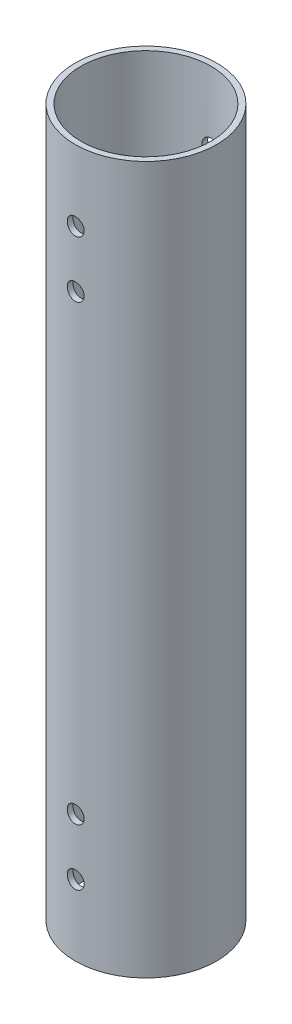
SolidWorks part; units mm, degrees
material "Thornel Mat VMA"
ref_plane "前视基准面" through (0, 0, 0) normal (0, 0, 1) x (1, 0, 0)
ref_plane "上视基准面" through (0, 0, 0) normal (0, 1, 0) x (1, 0, 0)
ref_plane "右视基准面" through (0, 0, 0) normal (1, 0, 0) x (0, 0, -1)
other "Configuration Table"
sketch "草图1" plane through (0, 0, 0) normal (0, 1, 0) x (1, 0, 0)
  circle A0 centre (0, 0) radius 25
  circle A1 centre (0, 0) radius 23
  dimension "D1" = 50
  dimension "D2" = 46
extrude "凸台-拉伸1" add sketch "草图1" along normal blind 250
sketch "草图2" plane through (0, 0, 0) normal (0, 0, 1) x (1, 0, 0)
  line L0 (-1005.3322, 125) -> (48994.6678, 125) construction
  line L1 (-25, 250) -> (-25, 0) construction
  line L2 (25, 0) -> (-25, 0) construction
  line L3 (25, 0) -> (25, 70) construction
  line L4 (25, 70) -> (-25, 70) construction
  line L5 (-25, 0) -> (-25, 70) construction
  line L6 (-25, 0) -> (25, 70) construction
  line L7 (25, 0) -> (-25, 70) construction
  line L8 (0, 25) -> (0, 45) construction
  circle A0 centre (0, 45) radius 3
  circle A1 centre (0, 25) radius 3
  circle A2 centre (0, 225) radius 3
  circle A3 centre (0, 205) radius 3
  point P13 (0, 35)
  dimension "D4" = 6
  dimension "D5" = 6
  dimension "D1" = 125
  dimension "D2" = 70
  dimension "D3" = 20
extrude "切除-拉伸1" cut sketch "草图2" against normal through all and the other way through all
